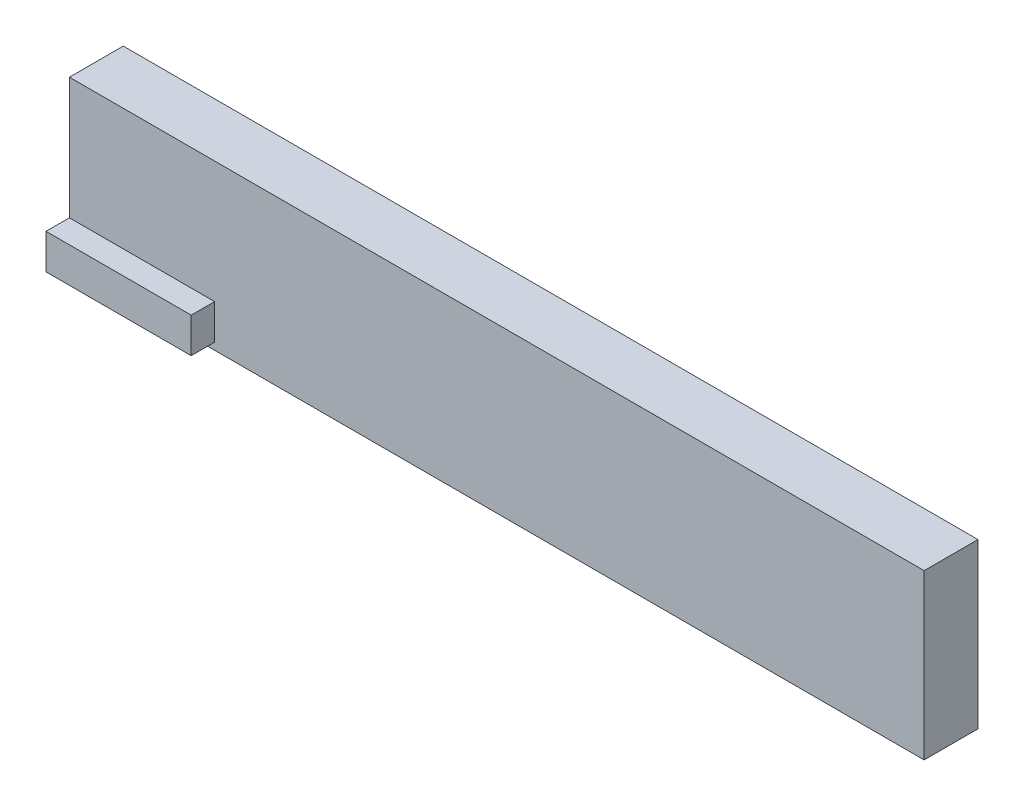
SolidWorks part; units mm, degrees
ref_plane "Front Plane" through (0, 0, 0) normal (0, 0, 1) x (1, 0, 0)
ref_plane "Top Plane" through (0, 0, 0) normal (0, 1, 0) x (1, 0, 0)
ref_plane "Right Plane" through (0, 0, 0) normal (1, 0, 0) x (0, 0, -1)
sketch "Sketch1" plane through (0, 0, 0) normal (0, 0, 1) x (1, 0, 0)
  line L1 (0, 0) -> (36.5, 0)
  line L2 (0, 0) -> (0, -7)
  line L3 (0, -7) -> (36.5, -7)
  line L4 (36.5, 0) -> (36.5, -7)
  dimension "D1" = 36.5
  dimension "D2" = 7
extrude "Boss-Extrude1" add sketch "Sketch1" along normal blind 2.3
sketch "Sketch2" plane through (0, 0, 2.3) normal (0, 0, 1) x (1, 0, 0)
  line L0 (0, -7) -> (36.5, -7) construction
  line L1 (0, -5.2) -> (6.2, -5.2)
  line L2 (0, -5.2) -> (0, -6.7)
  line L3 (0, -6.7) -> (6.2, -6.7)
  line L4 (6.2, -5.2) -> (6.2, -6.7)
  line L5 (0, 0) -> (0, -7) construction
  circle A0 centre (0.9197, -5.9814) radius 0.5 construction
  circle A1 centre (0.9197, -5.9814) radius 0.6 construction
  dimension "D1" = 6.2
  dimension "D4" = 1.2
  dimension "D5" = 1
  dimension "D2" = 1.8
  dimension "D3" = 1.5
extrude "Boss-Extrude2" add sketch "Sketch2" along normal blind 1
sketch "Sketch3" plane through (0, 0, 0) normal (-1, 0, 0) x (0, 0, 1)
  circle A0 centre (2.7799, -5.9343) radius 0.5
  dimension "D1" = 1
extrude "Cut-Extrude1" cut sketch "Sketch3" against normal blind 1
